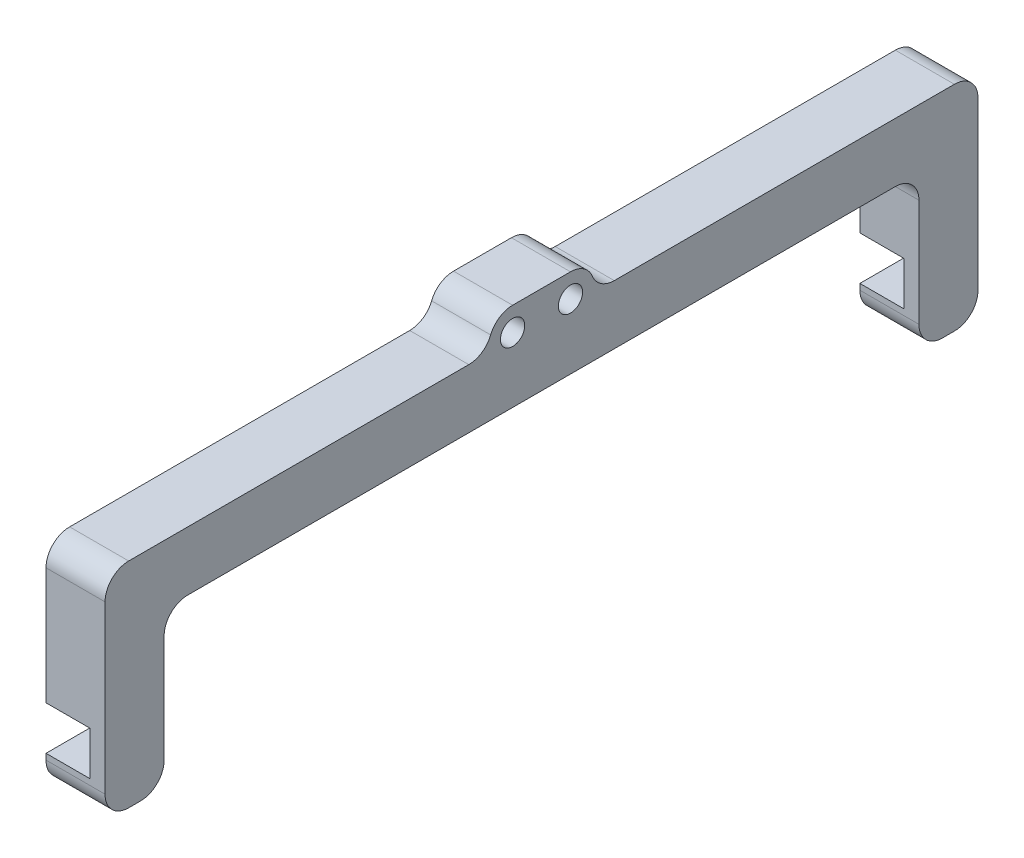
SolidWorks part; units mm, degrees
ref_plane "Front Plane" through (0, 0, 0) normal (0, 0, 1) x (1, 0, 0)
ref_plane "Top Plane" through (0, 0, 0) normal (0, 1, 0) x (1, 0, 0)
ref_plane "Right Plane" through (0, 0, 0) normal (1, 0, 0) x (0, 0, -1)
sketch "Sketch1" plane through (0, 0, 0) normal (1, 0, 0) x (0, 0, -1)
  line L0 (17.8, -5) -> (82.8, -5)
  line L1 (0, 0) -> (17.8, 0)
  line L4 (17.8, 0) -> (17.8, -5)
  line L9 (-65, -15) -> (82.8, -15)
  line L10 (82.8, -15) -> (82.8, -5)
  line L11 (0, 0) -> (0, -5)
  line L12 (0, -5) -> (-65, -5)
  line L13 (-65, -5) -> (-65, -15)
  dimension "D1" = 17.8
  dimension "D2" = 5
  dimension "D3" = 10
  dimension "D4" = 65
extrude "Boss-Extrude1" add sketch "Sketch1" along normal blind 10
sketch "Sketch3" plane through (10, 0, 0) normal (1, 0, 0) x (0, 0, -1)
  line L0 (0, -4) -> (17.8, -4) construction
  line L2 (17.8, -5) -> (17.8, 0) construction
  line L3 (17.8, 0) -> (0, 0) construction
  line L4 (0, 0) -> (0, -5) construction
  circle A0 centre (4, -4) radius 2.055
  circle A1 centre (13.8, -4) radius 2.055
  dimension "D4" = 4.11
  dimension "D1" = 4
  dimension "D2" = 4
  dimension "D3" = 4
extrude "Cut-Extrude1" cut sketch "Sketch3" against normal through all
sketch "Sketch5" plane through (10, 0, 0) normal (1, 0, 0) x (0, 0, -1)
  line L0 (-65, -15) -> (82.8, -15) construction
  line L1 (-65, -15) -> (-55, -15)
  line L2 (-65, -15) -> (-65, -28.8)
  line L3 (-65, -28.8) -> (-55, -28.8)
  line L4 (-55, -15) -> (-55, -28.8)
  line L5 (72.8, -15) -> (82.8, -15)
  line L6 (72.8, -15) -> (72.8, -28.8)
  line L7 (72.8, -28.8) -> (82.8, -28.8)
  line L8 (82.8, -15) -> (82.8, -28.8)
  dimension "D1" = 10
  dimension "D2" = 13.8
extrude "Boss-Extrude2" add sketch "Sketch5" against normal up to surface (10 mm away) up to face at (0, -4, -6.055)
sketch "Sketch10" plane through (10, 0, 0) normal (1, 0, 0) x (0, 0, -1)
  line L1 (-65, -28.8) -> (-55, -28.8)
  line L2 (-65, -28.8) -> (-65, -36.2)
  line L3 (-65, -36.2) -> (-55, -36.2)
  line L4 (-55, -28.8) -> (-55, -36.2)
  dimension "D1" = 7.4
extrude "Boss-Extrude5" add sketch "Sketch10" against normal blind 2.5289
sketch "Sketch11" plane through (10, 0, 0) normal (1, 0, 0) x (0, 0, -1)
  line L1 (-65, -36.2) -> (-55, -36.2)
  line L2 (-65, -36.2) -> (-65, -41.2)
  line L3 (-65, -41.2) -> (-55, -41.2)
  line L4 (-55, -36.2) -> (-55, -41.2)
  dimension "D1" = 5
extrude "Boss-Extrude6" add sketch "Sketch11" against normal up to surface (10 mm away) up to face at (0, -4, -6.055)
ref_plane "Plane1" through (0, 0, -8.9) normal (0, 0, 1) x (1, 0, 0)
mirror "Mirror1" about plane through (0, 0, -8.9) normal (0, 0, 1) of "Boss-Extrude5", "Boss-Extrude6"
fillet "Fillet1" radius 4 2 edges at (5, 0, -17.8) (5, 0, 0)
fillet "Fillet2" radius 4 8 edges at (5, -41.2, -82.8) (5, -41.2, -72.8) (5, -15, -72.8) (5, -15, 55) (5, -41.2, 55) (5, -41.2, 65) (5, -5, -82.8) (5, -5, 65)
fillet "Fillet3" radius 4 2 edges at (5, -5, -17.8) (5, -5, 0)
